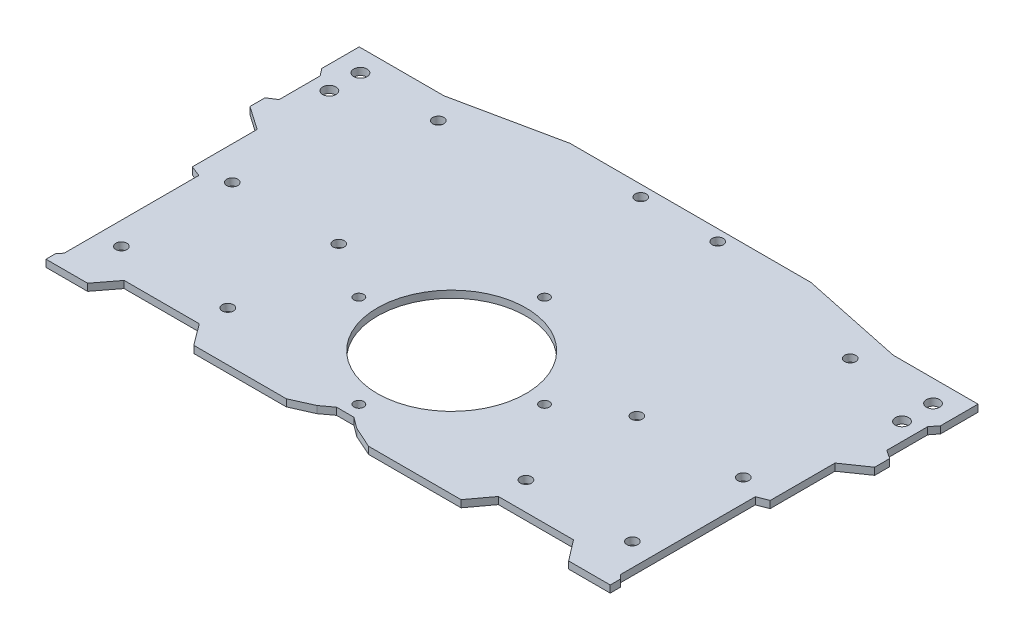
SolidWorks part; units mm, degrees
ref_plane "Alzado" through (0, 0, 0) normal (0, 0, 1) x (1, 0, 0)
ref_plane "Planta" through (0, 0, 0) normal (0, 1, 0) x (1, 0, 0)
ref_plane "Vista lateral" through (0, 0, 0) normal (1, 0, 0) x (0, 0, -1)
sketch "Croquis1" plane through (0, 0, 0) normal (0, 1, 0) x (1, 0, 0)
  line L0 (63.6075, 3.859) -> (63.6075, 27.859) construction
  line L1 (65.571, 3.859) -> (61.644, 3.859)
  line L2 (61.644, 3.859) -> (59.104, 1.975)
  line L3 (59.104, 1.975) -> (54.333, -0.156)
  line L4 (54.333, -0.156) -> (33.47, -0.156)
  line L5 (33.47, -0.156) -> (29.893, 4.67)
  line L6 (29.893, 4.67) -> (12.9495, 4.67)
  line L7 (12.9495, 4.67) -> (9.375, 0)
  line L8 (9.375, 0) -> (0, 0)
  line L9 (0, 0) -> (0, 2.277)
  line L10 (0, 2.277) -> (0.872, 3.207)
  line L11 (0.872, 3.207) -> (0.872, 21.491)
  line L12 (0.872, 21.491) -> (0.872, 33.5873)
  line L13 (0.872, 33.5873) -> (-1.537, 34.54)
  line L14 (-1.537, 34.54) -> (-1.537, 49.146)
  line L15 (-1.537, 49.146) -> (-6.825, 52.811)
  line L16 (-6.825, 52.811) -> (-6.825, 56.199)
  line L17 (-6.825, 56.199) -> (-4.887, 57.46)
  line L18 (-4.887, 57.46) -> (-4.887, 66.704)
  line L19 (-4.887, 66.704) -> (-6.154, 68.325)
  line L20 (-6.154, 68.325) -> (-6.154, 76.772)
  line L21 (-6.154, 76.772) -> (-2.9874, 76.772)
  line L22 (-2.9874, 76.772) -> (12.9495, 76.772)
  line L23 (12.9495, 76.772) -> (36.47, 81.705)
  line L24 (36.47, 81.705) -> (90.745, 81.705)
  line L25 (114.2655, 76.772) -> (90.745, 81.705)
  line L26 (130.2024, 76.772) -> (114.2655, 76.772)
  line L27 (133.369, 76.772) -> (130.2024, 76.772)
  line L28 (133.369, 68.325) -> (133.369, 76.772)
  line L29 (132.102, 66.704) -> (133.369, 68.325)
  line L30 (132.102, 57.46) -> (132.102, 66.704)
  line L31 (134.04, 56.199) -> (132.102, 57.46)
  line L32 (134.04, 52.811) -> (134.04, 56.199)
  line L33 (128.752, 49.146) -> (134.04, 52.811)
  line L34 (128.752, 34.54) -> (128.752, 49.146)
  line L35 (126.343, 33.5873) -> (128.752, 34.54)
  line L36 (126.343, 21.491) -> (126.343, 33.5873)
  line L37 (126.343, 3.207) -> (126.343, 21.491)
  line L38 (127.215, 2.277) -> (126.343, 3.207)
  line L39 (127.215, 0) -> (127.215, 2.277)
  line L40 (117.84, 0) -> (127.215, 0)
  line L41 (114.2655, 4.67) -> (117.84, 0)
  line L42 (97.322, 4.67) -> (114.2655, 4.67)
  line L43 (93.745, -0.156) -> (97.322, 4.67)
  line L44 (72.882, -0.156) -> (93.745, -0.156)
  line L45 (68.111, 1.975) -> (72.882, -0.156)
  line L46 (65.571, 3.859) -> (68.111, 1.975)
  line L47 (114.2655, 76.772) -> (90.745, 81.705)
  line L48 (130.2024, 76.772) -> (114.2655, 76.772)
  line L49 (133.369, 76.772) -> (130.2024, 76.772)
  line L50 (133.369, 68.325) -> (133.369, 76.772)
  line L51 (132.102, 66.704) -> (133.369, 68.325)
  line L52 (132.102, 57.46) -> (132.102, 66.704)
  line L53 (134.04, 56.199) -> (132.102, 57.46)
  line L54 (134.04, 52.811) -> (134.04, 56.199)
  line L55 (128.752, 49.146) -> (134.04, 52.811)
  line L56 (128.752, 34.54) -> (128.752, 49.146)
  line L57 (126.343, 33.5873) -> (128.752, 34.54)
  line L58 (126.343, 21.491) -> (126.343, 33.5873)
  line L59 (126.343, 3.207) -> (126.343, 21.491)
  line L60 (127.215, 2.277) -> (126.343, 3.207)
  line L61 (127.215, 0) -> (127.215, 2.277)
  line L62 (117.84, 0) -> (127.215, 0)
  line L63 (114.2655, 4.67) -> (117.84, 0)
  line L64 (97.322, 4.67) -> (114.2655, 4.67)
  line L65 (93.745, -0.156) -> (97.322, 4.67)
  line L66 (72.882, -0.156) -> (93.745, -0.156)
  line L67 (68.111, 1.975) -> (72.882, -0.156)
  circle A0 centre (5.998, 11.001) radius 1.25
  circle A1 centre (5.998, 36.001) radius 1.25
  circle A2 centre (121.217, 36.001) radius 1.25
  circle A3 centre (121.217, 11.001) radius 1.25
  circle A4 centre (-0.951, 71.841) radius 1.5
  circle A5 centre (-0.951, 64.841) radius 1.5
  circle A6 centre (17.167, 71.285) radius 1.25
  circle A7 centre (54.929, 79.176) radius 1.25
  circle A8 centre (29.998, 36.001) radius 1.25
  circle A9 centre (29.998, 11.001) radius 1.25
  circle A10 centre (97.217, 11.001) radius 1.25
  circle A11 centre (97.217, 36.001) radius 1.25
  circle A12 centre (72.286, 79.176) radius 1.25
  circle A13 centre (110.048, 71.285) radius 1.25
  circle A14 centre (128.166, 64.841) radius 1.5
  circle A15 centre (128.166, 71.841) radius 1.5
  circle A16 centre (121.217, 36.001) radius 1.25
  circle A17 centre (121.217, 11.001) radius 1.25
  circle A18 centre (63.6075, 27.859) radius 16.75
  circle A19 centre (63.6075, 48.7793) radius 1.1
  circle A20 centre (84.5278, 27.859) radius 1.1
  circle A23 centre (63.6075, 6.9387) radius 1.1
  circle A24 centre (42.6872, 27.859) radius 1.1
  point P36 (63.6075, 81.705)
  dimension "D1" = 2.5
  dimension "D3" = 33.5
  dimension "D2" = 24
  dimension "D4" = 7
extrude "Saliente-Extruir1" add sketch "Croquis1" along normal blind 1.6
